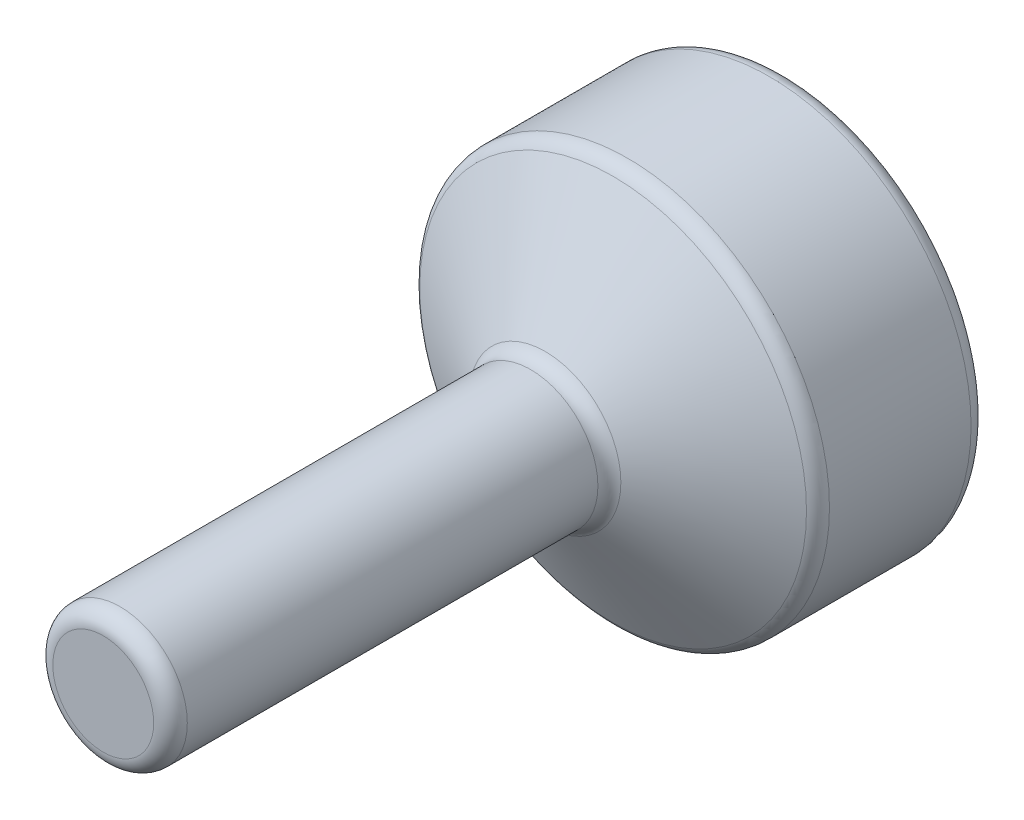
SolidWorks part; units mm, degrees
ref_plane "Front Plane" through (0, 0, 0) normal (0, 0, 1) x (1, 0, 0)
ref_plane "Top Plane" through (0, 0, 0) normal (0, 1, 0) x (1, 0, 0)
ref_plane "Right Plane" through (0, 0, 0) normal (1, 0, 0) x (0, 0, -1)
sketch "Sketch1" plane through (0, 0, 0) normal (0, 1, 0) x (1, 0, 0)
  line L0 (0, 0) -> (3.048, 0)
  line L1 (3.048, 0) -> (3.048, -2.54)
  line L2 (3.048, -2.54) -> (1.016, -3.7132)
  line L3 (1.016, -3.7132) -> (1.016, -10.3172)
  line L4 (1.016, -10.3172) -> (0, -10.3172)
  line L5 (0, -10.3172) -> (0, 0)
  dimension "D1" = 6.604
  dimension "D2" = 2.54
  dimension "D3" = 3.048
  dimension "D4" = 1.016
  dimension "D5" = 120
revolve "Revolve1" add sketch "Sketch1" angle 360 about L5
fillet "Fillet1" radius 0.254 4 edges at (1.016, 0, 10.3172) (3.048, 0, 0) (1.016, 0, 3.7132) (3.048, 0, 2.54)
